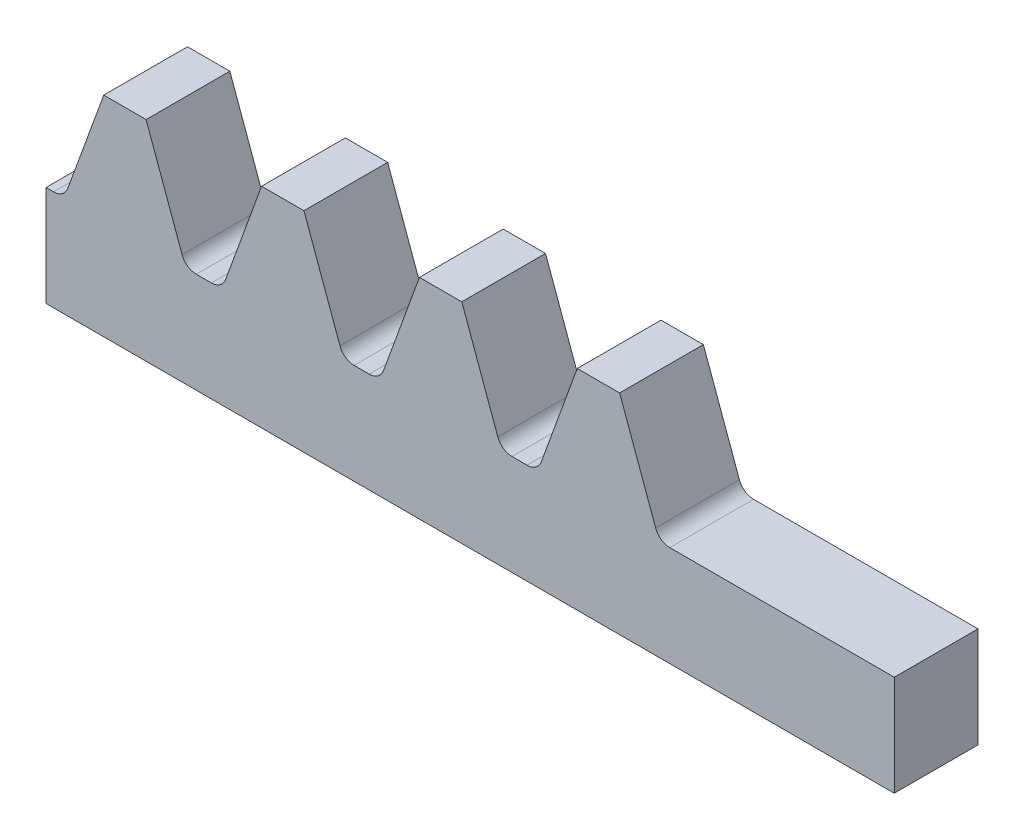
SolidWorks part; units mm, degrees
ref_plane "Front Plane" through (0, 0, 0) normal (0, 0, 1) x (1, 0, 0)
ref_plane "Top Plane" through (0, 0, 0) normal (0, 1, 0) x (1, 0, 0)
ref_plane "Right Plane" through (0, 0, 0) normal (1, 0, 0) x (0, 0, -1)
sketch "Sketch1" plane through (0, 0, 0) normal (0, 0, 1) x (1, 0, 0)
  line L0 (138.5786, 12) -> (138.5786, 0)
  line L5 (0, 25.002) -> (105.7787, 25.002) construction
  line L18 (49.2287, 25.002) -> (53.5299, 13.1844)
  line L19 (44.1713, 25.002) -> (49.2287, 25.002)
  line L20 (44.1713, 25.002) -> (39.8701, 13.1844)
  line L21 (68.0787, 25.002) -> (72.3799, 13.1844)
  line L22 (63.0213, 25.002) -> (68.0787, 25.002)
  line L23 (63.0213, 25.002) -> (58.7201, 13.1844)
  line L24 (86.9287, 25.002) -> (91.2299, 13.1844)
  line L25 (81.8713, 25.002) -> (86.9287, 25.002)
  line L26 (81.8713, 25.002) -> (77.5701, 13.1844)
  line L27 (105.7787, 25.002) -> (110.0799, 13.1844)
  line L28 (100.7213, 25.002) -> (105.7787, 25.002)
  line L29 (100.7213, 25.002) -> (96.4201, 13.1844)
  line L36 (37.275, 12) -> (38.1786, 12)
  line L37 (55.2214, 12) -> (57.0286, 12)
  line L38 (74.0714, 12) -> (75.8786, 12)
  line L39 (92.9214, 12) -> (94.7286, 12)
  line L40 (111.7714, 12) -> (113.5786, 12)
  line L43 (113.5786, 12) -> (138.5786, 12)
  line L44 (37.275, 0) -> (138.5786, 0)
  line L46 (37.275, 12) -> (37.275, 0)
  arc A4 (53.5299, 13.1844) -> (55.2214, 12) centre (55.2214, 13.8) ccw
  arc A5 (39.8701, 13.1844) -> (38.1786, 12) centre (38.1786, 13.8) cw
  arc A6 (72.3799, 13.1844) -> (74.0714, 12) centre (74.0714, 13.8) ccw
  arc A7 (58.7201, 13.1844) -> (57.0286, 12) centre (57.0286, 13.8) cw
  arc A8 (91.2299, 13.1844) -> (92.9214, 12) centre (92.9214, 13.8) ccw
  arc A9 (77.5701, 13.1844) -> (75.8786, 12) centre (75.8786, 13.8) cw
  arc A10 (110.0799, 13.1844) -> (111.7714, 12) centre (111.7714, 13.8) ccw
  arc A11 (96.4201, 13.1844) -> (94.7286, 12) centre (94.7286, 13.8) cw
  dimension "D1" = 25
extrude "Boss-Extrude1" add sketch "Sketch1" along normal blind 10
